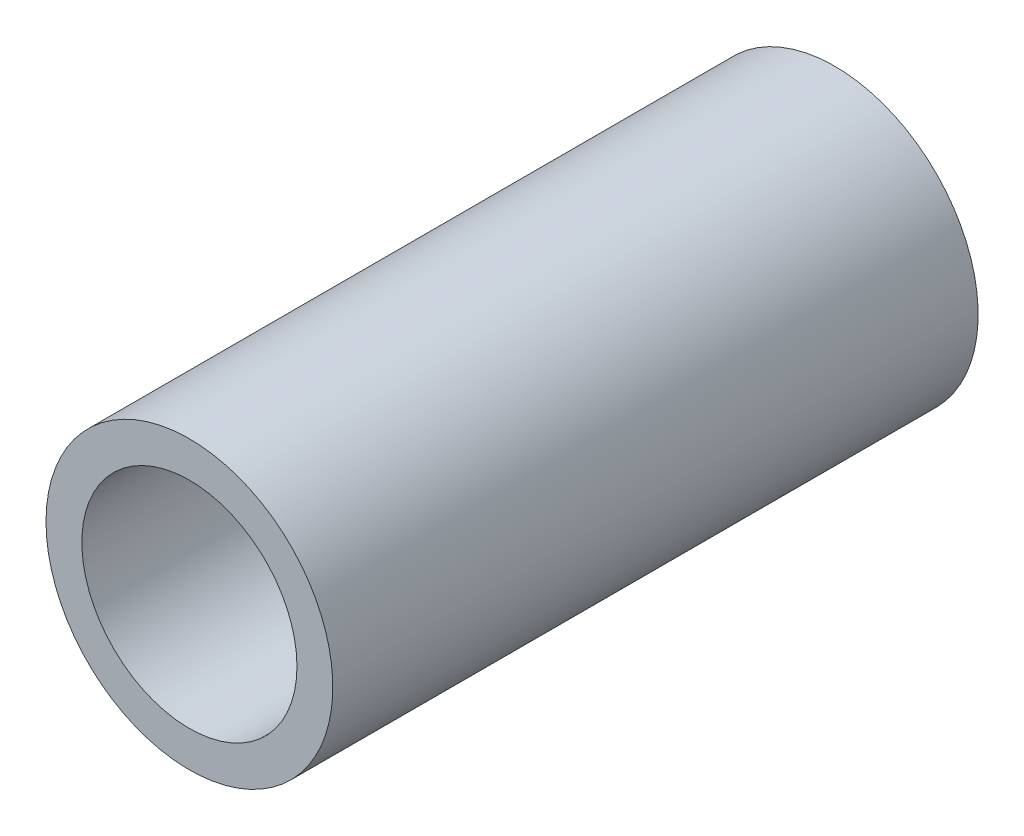
SolidWorks part; units mm, degrees
ref_plane "Front Plane" through (0, 0, 0) normal (0, 0, 1) x (1, 0, 0)
ref_plane "Top Plane" through (0, 0, 0) normal (0, 1, 0) x (1, 0, 0)
ref_plane "Right Plane" through (0, 0, 0) normal (1, 0, 0) x (0, 0, -1)
sketch "Sketch1" plane through (0, 0, 0) normal (0, 0, 1) x (1, 0, 0)
  circle A0 centre (0, 0) radius 20
  dimension "D1" = 40
extrude "Boss-Extrude1" add sketch "Sketch1" along normal blind 90 contours A0
sketch "Sketch2" plane through (0, 0, 90) normal (0, 0, 1) x (1, 0, 0)
  circle A0 centre (0, 0) radius 15
  dimension "D1" = 30
extrude "Cut-Extrude1" cut sketch "Sketch2" against normal blind 90
